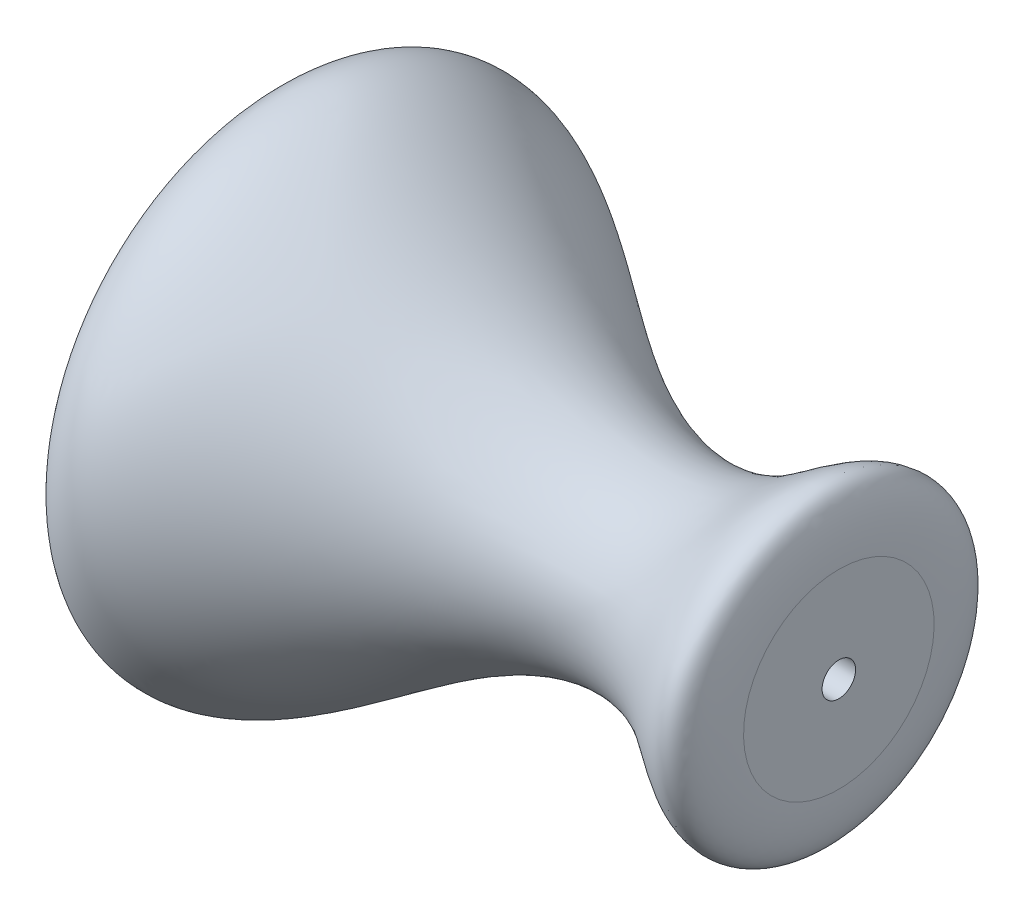
SolidWorks part; units mm, degrees
ref_plane "Plan de face" through (0, 0, 0) normal (0, 0, 1) x (1, 0, 0)
ref_plane "Plan de dessus" through (0, 0, 0) normal (0, 1, 0) x (1, 0, 0)
ref_plane "Plan de droite" through (0, 0, 0) normal (1, 0, 0) x (0, 0, -1)
sketch "Esquisse1" plane through (0, 0, 0) normal (0, 0, 1) x (1, 0, 0)
  line L0 (0, 0) -> (124.1416, 0) construction
  line L1 (115.7242, 17.8177) -> (115.7242, 3.1365)
  line L2 (115.7242, 3.1365) -> (56.9991, 3.1365)
  line L3 (56.9991, 3.1365) -> (53.8626, 0)
  line L4 (53.8626, 0) -> (0, 0)
  spline S0 degree 3 poles (0, 0) (6.4823, 79.3588) (40.4394, 24.5477) (95.7049, 12.9337) (115.6073, 37.6825) (115.7242, 17.8177) knots 0 0 0 0 0.608952 0.823188 1 1 1 1
  point P4 (24.9325, 46.4246)
  point P12 (63.0349, 23.0283)
  point P13 (97.2603, 21.2903)
revolve "Révolution1" add sketch "Esquisse1" angle 360 about L4
